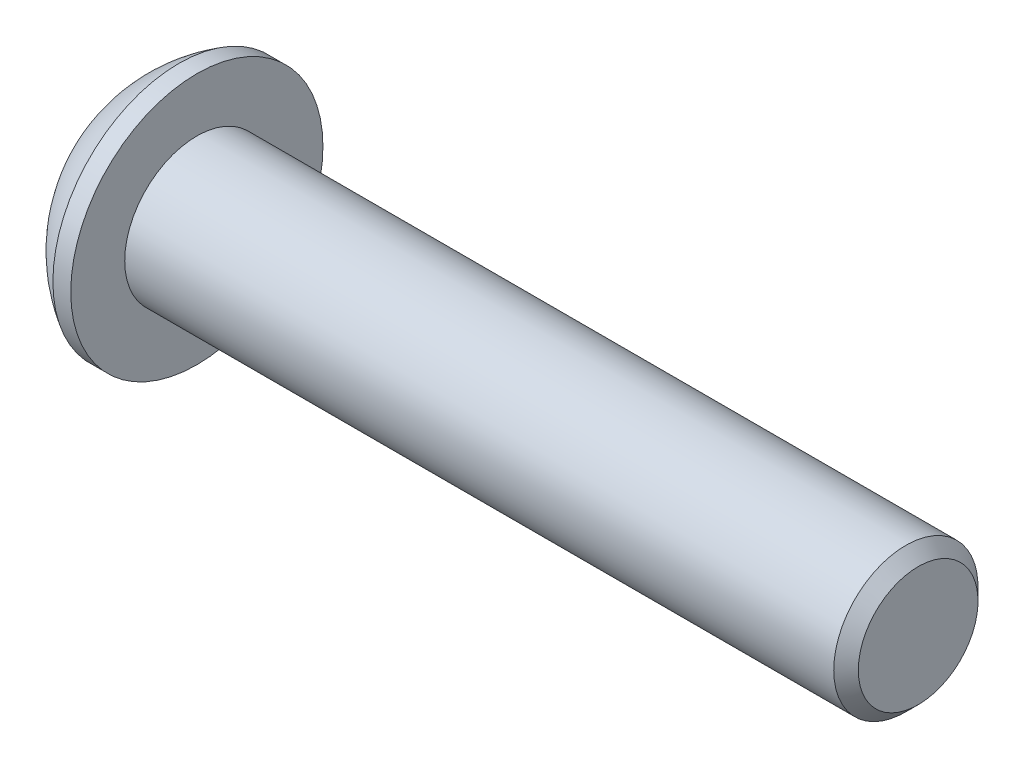
SolidWorks part; units mm, degrees
ref_plane "Plane1" through (0, 0, 0) normal (0, 0, 1) x (1, 0, 0)
ref_plane "Plane2" through (0, 0, 0) normal (0, 1, 0) x (1, 0, 0)
ref_plane "Plane3" through (0, 0, 0) normal (1, 0, 0) x (0, 0, -1)
sketch "BodySke" plane through (0, 0, 0) normal (0, 0, 1) x (1, 0, 0)
  line L0 (35.1028, 0) -> (35.1028, 2.634)
  line L1 (34.5618, 3.175) -> (3.3528, 3.175)
  line L2 (3.3528, 3.175) -> (3.3528, 5.5499)
  line L3 (3.3528, 5.5499) -> (2.5654, 5.5499)
  line L4 (0, 0) -> (101.6, 0) construction
  line L5 (3.3528, -5.5499) -> (2.5654, -5.5499) construction
  line L6 (55.6768, -3.175) -> (3.3528, -3.175) construction
  line L7 (35.1028, 0) -> (0, 0)
  line L8 (0, 2.775) -> (0, -2.775) construction
  line L9 (0, 0) -> (0, 2.775)
  line L10 (35.1028, 2.634) -> (34.5618, 3.175)
  line L11 (35.1028, -2.634) -> (34.5618, -3.175) construction
  line L12 (4.2596, 9.525) -> (4.2596, -3.175) construction
  line L13 (3.3528, 9.525) -> (3.3528, -3.175) construction
  arc A1 (0, 2.775) -> (2.5654, 5.5499) centre (5.7851, 0) cw
  dimension "Diameter" = 6.35
  dimension "Length" = 31.75
  dimension "Head_dia" = 11.0998
  dimension "D1" = 5.5499
  dimension "Head_ht" = 3.3528
  dimension "Head_side_ht" = 0.7874
  dimension "Minor_dia" = 5.268
  dimension "Body_ch_ang" = 45
  dimension "Advance" = 0.9068
  dimension "Thread_nom" = 31.75
revolve "BaseBody" add sketch "BodySke" angle 360 about L4
cosmetic thread "ThreadCosmetic" [suppressed] parameters "Thread_length"=30.8432, "Thread_minor"=5.268
sketch "Sketch2" plane through (0, 0, 0) normal (0, 0, 1) x (1, 0, 0)
  line L0 (0, 1.9812) -> (2.2098, 1.9812)
  line L1 (2.2098, 1.9812) -> (3.3536, 0)
  line L3 (3.3536, 0) -> (0, 0)
  line L4 (0, 0) -> (0, 1.9812)
  line L5 (0, -1.9812) -> (2.2098, -1.9812) construction
  line L6 (0, 0) -> (47.625, 0) construction
  dimension "D2" = 60
  dimension "PreBroach_depth" = 2.2098
  dimension "PreBroach_dia" = 3.9624
revolve "PreBroach" cut sketch "Sketch2" angle 360 about L6
sketch "Sketch3" plane through (0, 0, 0) normal (1, 0, 0) x (0, 0, -1)
  line L0 (-1.9812, -1.1438) -> (-1.9812, 1.1438)
  line L1 (-1.9812, 1.1438) -> (0, 2.2877)
  line L2 (0, 2.2877) -> (1.9812, 1.1438)
  line L3 (1.9812, 1.1438) -> (1.9812, -1.1438)
  line L4 (1.9812, -1.1438) -> (0, -2.2877)
  line L5 (0, -2.2877) -> (-1.9812, -1.1438)
  dimension "Hex_size" = 3.9624
  dimension "D3" = 3.9624
  dimension "D1" = 1.9812
  dimension "D2" = 1.9812
extrude "Hex" cut sketch "Sketch3" along normal blind 2.2098
sketch "Sketch4" plane through (0, 9.525, 0) normal (1, 0, 0) x (0, 0, -1)
  line L0 (0, -9.525) -> (2.3876, -9.525)
  line L1 (0, -9.525) -> (6.1484, -5.9752) construction
  line L2 (0, -9.525) -> (1.1938, -7.4573)
  line L3 (1.9883, -8.949) -> (2.2704, -8.7861)
  line L4 (1.493, -8.0911) -> (1.7751, -7.9282)
  arc A0 (1.9883, -8.949) -> (1.493, -8.0911) centre (0, -9.525) ccw
  arc A1 (2.3876, -9.525) -> (2.2704, -8.7861) centre (0, -9.525) ccw
  arc A2 (1.1938, -7.4573) -> (1.7751, -7.9282) centre (0, -9.525) cw
  dimension "Spline_n_dim" = 4.1402
  dimension "Spline_m_dim" = 4.7752
  dimension "D1" = 30
  dimension "D2" = 60
  dimension "Spline_p_dim" = 0.9906
  dimension "D3" = 0.4953
extrude "Spline" [suppressed] cut sketch "Sketch4" along normal blind 2.2098
pattern_circular "CirPattern1" [suppressed] count 6 every 60 about axis through (0, 0, 0) along (1, 0, 0)
sketch "ThdSchSke" plane through (0, 0, 0) normal (0, 0, 1) x (1, 0, 0)
  line L0 (4.2596, -2.634) -> (3.8808, -3.175)
  line L1 (4.2596, -2.634) -> (4.6384, -3.175)
  line L2 (4.6384, -3.175) -> (4.6384, -3.9688)
  line L3 (-3.175, 0) -> (5.1513, 0) construction
  line L5 (4.6384, -3.9688) -> (3.8808, -3.9688)
  line L6 (3.8808, -3.9688) -> (3.8808, -3.175)
  dimension "Diameter" = 6.35
  dimension "Thread_minor" = 5.268
  dimension "SideAngle" = 55
  dimension "VeeAngle" = 70
  dimension "Overcut" = 7.9375
  dimension "Start" = 4.2596
revolve "ThreadSchematic" [suppressed] cut sketch "ThdSchSke" angle 360 about L3
pattern_linear "ThdSchPat" [suppressed]
equation "\"D1@BodySke\" = \"Head_dia@BodySke\" * .5"
equation "\"Thread_minor@ThreadCosmetic\" = \"Minor_dia@BodySke\""
equation "\"D1@Sketch3\" = \"Hex_size@Sketch3\" / 2"
equation "\"D2@Sketch3\" = \"D1@Sketch3\""
equation "\"D3@Sketch3\" = \"Hex_size@Sketch3\""
equation "\"D3@Sketch4\" = \"Spline_p_dim@Sketch4\" / 2"
equation "\"D1@Sketch4\" = \"D2@Sketch4\" / 2"
equation "\"Thread_length@ThreadCosmetic\" = ((sgn( (\"Length@BodySke\" - \"Advance@BodySke\" ) - \"Thread_nom@BodySke\" )-1)*( (\"Length@BodySke\" - \"Advance@BodySke\" ) - \"Thread_nom@BodySke\" ))/-2+ \"Thread_nom@BodySke\""
equation "\"Thread_minor@ThdSchSke\" = \"Minor_dia@BodySke\""
equation "\"Diameter@ThdSchSke\" = \"Diameter@BodySke\""
equation "\"Overcut@ThdSchSke\" = \"Diameter@BodySke\" * 1.25"
equation "\"Start@ThdSchSke\" = \"Head_ht@BodySke\" + \"Length@BodySke\" - \"Thread_length@ThreadCosmetic\"  '---Non-countersunk---"
equation "\"Num_threads@ThdSchPat\" = int( \"Thread_length@ThreadCosmetic\" / \"Advance@BodySke\" + 0.999 )  + 1"
equation "\"Advance@ThdSchPat\" = \"Thread_length@ThreadCosmetic\" /  (\"Num_threads@ThdSchPat\" - 1) 'relax it"
equation "\"Num_threads@ThdSchPat\" = \"Num_threads@ThdSchPat\" - sgn( \"Num_threads@ThdSchPat\" - 1) '---chamfered tips only---"
